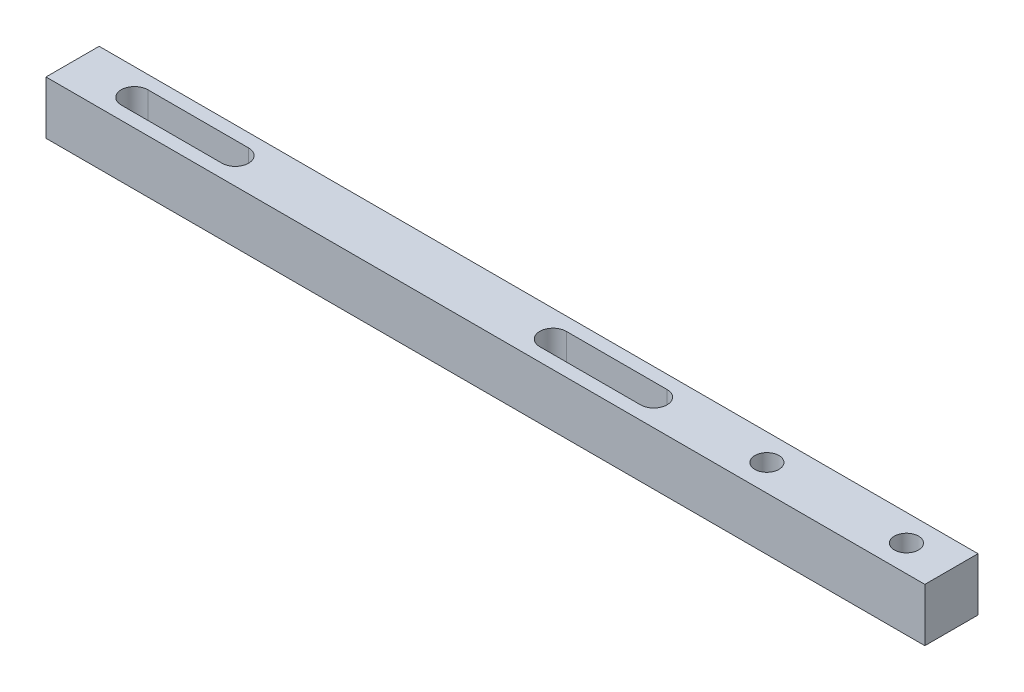
SolidWorks part; units mm, degrees
ref_plane "Alzado" through (0, 0, 0) normal (0, 0, 1) x (1, 0, 0)
ref_plane "Planta" through (0, 0, 0) normal (0, 1, 0) x (1, 0, 0)
ref_plane "Vista lateral" through (0, 0, 0) normal (1, 0, 0) x (0, 0, -1)
sketch "Croquis2" plane through (0, 0, 0) normal (1, 0, 0) x (0, 0, -1)
  line L1 (12.7, -12.7) -> (-12.7, -12.7)
  line L2 (12.7, -12.7) -> (12.7, 12.7)
  line L3 (12.7, 12.7) -> (-12.7, 12.7)
  line L4 (-12.7, -12.7) -> (-12.7, 12.7)
  line L5 (12.7, -12.7) -> (-12.7, 12.7) construction
  line L6 (12.7, 12.7) -> (-12.7, -12.7) construction
  point P0 (0, 0)
  dimension "D1" = 25.4
  dimension "D2" = 25.4
extrude "Saliente-Extruir1" add sketch "Croquis2" along normal mid plane 420
sketch "Croquis3" plane through (0, 12.7, 0) normal (0, 1, 0) x (1, 0, 0)
  line L0 (-180.3931, 0) -> (-132.2336, 0) construction
  line L1 (-180.3931, 6.35) -> (-132.2336, 6.35)
  line L2 (-180.3931, -6.35) -> (-132.2336, -6.35)
  line L3 (19.6069, 0) -> (67.7664, 0) construction
  line L4 (19.6069, 6.35) -> (67.7664, 6.35)
  line L5 (19.6069, -6.35) -> (67.7664, -6.35)
  arc A0 (-180.3931, 6.35) -> (-180.3931, -6.35) centre (-180.3931, 0) ccw
  arc A1 (-132.2336, -6.35) -> (-132.2336, 6.35) centre (-132.2336, 0) ccw
  arc A2 (19.6069, 6.35) -> (19.6069, -6.35) centre (19.6069, 0) ccw
  arc A3 (67.7664, -6.35) -> (67.7664, 6.35) centre (67.7664, 0) ccw
  circle A4 centre (121.8053, 0) radius 5.7656
  circle A5 centre (188.5045, 0) radius 5.7656
  point P2 (-156.3133, 0)
  point P12 (43.6867, 0)
  point P19 (121.8053, 0)
  dimension "D1" = 6.35
  dimension "D2" = 2
extrude "Cortar-Extruir1" cut sketch "Croquis3" against normal through all
